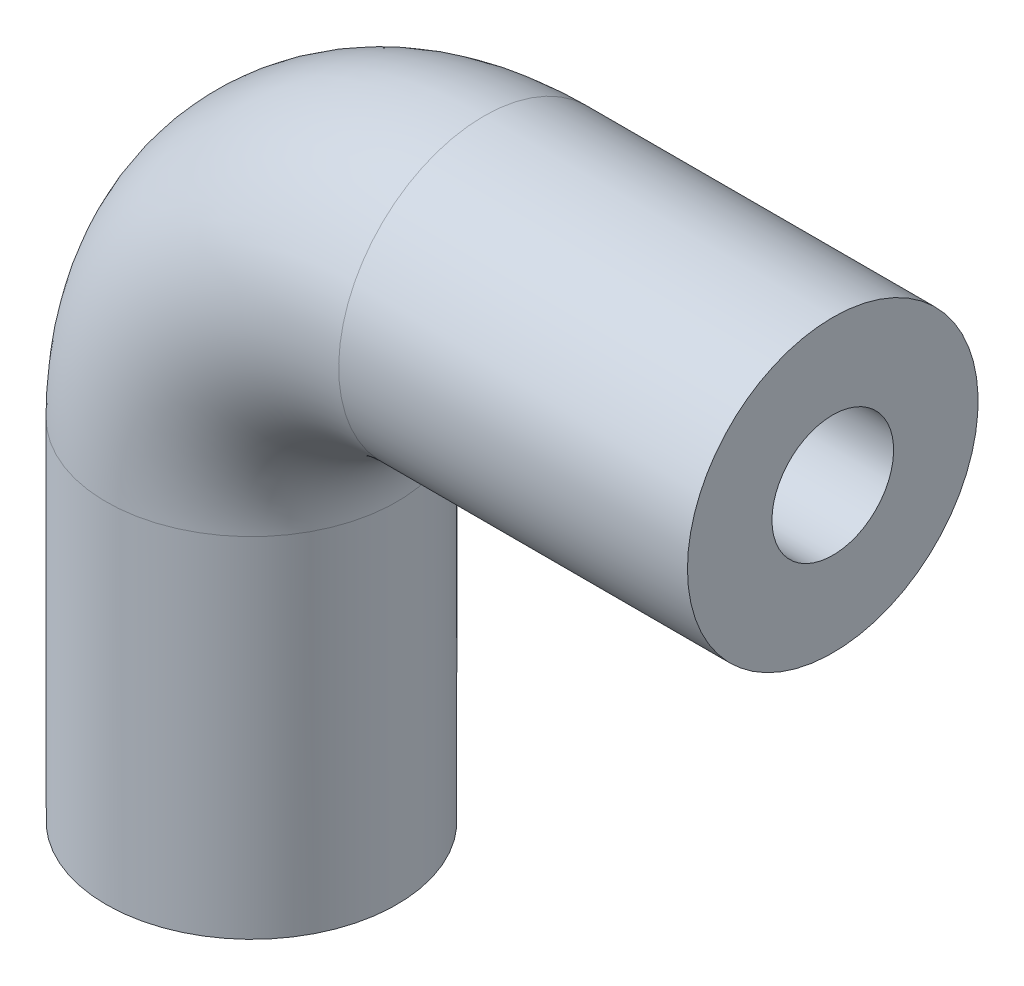
SolidWorks part; units mm, degrees
ref_plane "前视基准面" through (0, 0, 0) normal (0, 0, 1) x (1, 0, 0)
ref_plane "上视基准面" through (0, 0, 0) normal (0, 1, 0) x (1, 0, 0)
ref_plane "右视基准面" through (0, 0, 0) normal (1, 0, 0) x (0, 0, -1)
sketch "草图1" plane through (0, 0, 0) normal (0, 0, 1) x (1, 0, 0)
  line L0 (0, 0) -> (0, 12)
  line L1 (8, 20) -> (20, 20)
  arc A0 (0, 12) -> (8, 20) centre (8, 12) cw
  dimension "D2" = 8
  dimension "D1" = 12
sketch "草图2" plane through (0, 0, 0) normal (0, 1, 0) x (1, 0, 0)
  circle A0 centre (0, 0) radius 5
  circle A1 centre (0, 0) radius 2.0927
  dimension "D1" = 10
sweep "扫描1" add profiles "草图2" path "草图1"
